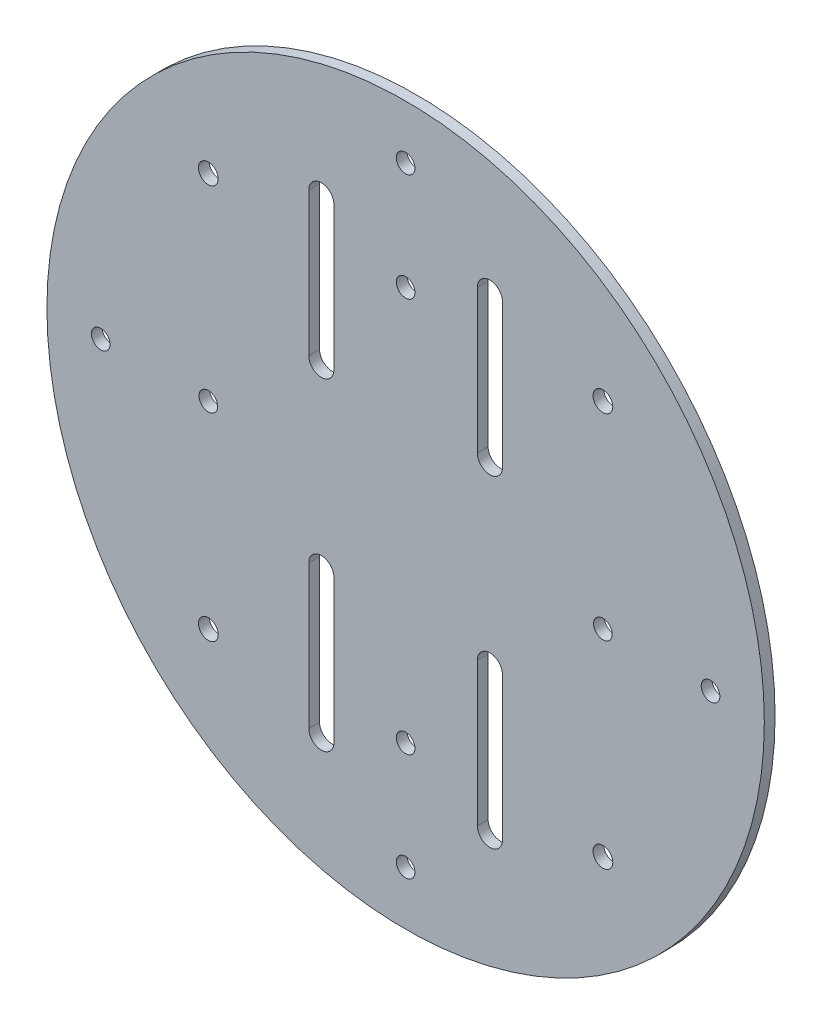
SolidWorks part; units mm, degrees
ref_plane "Ön Düzlem" through (0, 0, 0) normal (0, 0, 1) x (1, 0, 0)
ref_plane "Üst Düzlem" through (0, 0, 0) normal (0, 1, 0) x (1, 0, 0)
ref_plane "Sağ Düzlem" through (0, 0, 0) normal (1, 0, 0) x (0, 0, -1)
sketch "Çizim1" plane through (0, 0, 0) normal (0, 0, 1) x (1, 0, 0)
  circle A0 centre (0, 0) radius 100
  dimension "D1" = 200
extrude "Yükseklik-Ekstrüzyon1" add sketch "Çizim1" along normal blind 30
hole_wizard "M5 Helisarmal için Zıvana matkabı1" positions "Çizim7" profile "Çizim8" hole size "M5x0.8" standard "ANSI Metrik" end condition through all
sketch "Çizim7" plane through (0, 0, 30) normal (0, 0, 1) x (1, 0, 0)
  point P0 (-85, 0)
  point P2 (-55, 0)
  point P4 (0, 55)
  point P6 (0, 85)
  point P8 (55, 0)
  point P10 (85, 0)
  point P12 (0, -55)
  point P14 (0, -85)
  dimension "D1" = 85
  dimension "D2" = 55
  dimension "D3" = 55
  dimension "D4" = 85
  dimension "D5" = 85
  dimension "D6" = 55
  dimension "D7" = 85
  dimension "D8" = 55
sketch "Çizim8" plane through (-85, 0, 30) normal (1, 0, 0) x (0, -1, 0)
  line L0 (0, 0) -> (0, 30)
  line L1 (0, 30) -> (2.6, 30)
  line L2 (2.6, 30) -> (2.6, 0)
  line L5 (2.6, 0) -> (0, 0)
  line L11 (0, -6.35) -> (0, 107.95) construction
  dimension "Thru Hole Dia." = 5.2
  dimension "Thru Hole Depth" = 30
sketch "Çizim9" plane through (0, 0, 30) normal (0, 0, 1) x (1, 0, 0)
  line L0 (23.5, 65) -> (23.5, 25) construction
  line L1 (27, 65) -> (27, 25)
  line L2 (20, 65) -> (20, 25)
  line L3 (-23.5, 65) -> (-23.5, 25) construction
  line L4 (-20, 65) -> (-20, 25)
  line L5 (-27, 65) -> (-27, 25)
  line L6 (-23.5, -25) -> (-23.5, -65) construction
  line L7 (-20, -25) -> (-20, -65)
  line L8 (-27, -25) -> (-27, -65)
  line L9 (23.5, -65) -> (23.5, -25) construction
  line L10 (20, -65) -> (20, -25)
  line L11 (27, -65) -> (27, -25)
  arc A0 (27, 65) -> (20, 65) centre (23.5, 65) ccw
  arc A1 (20, 25) -> (27, 25) centre (23.5, 25) ccw
  arc A2 (-20, 65) -> (-27, 65) centre (-23.5, 65) ccw
  arc A3 (-27, 25) -> (-20, 25) centre (-23.5, 25) ccw
  arc A4 (-20, -25) -> (-27, -25) centre (-23.5, -25) ccw
  arc A5 (-27, -65) -> (-20, -65) centre (-23.5, -65) ccw
  arc A6 (20, -65) -> (27, -65) centre (23.5, -65) ccw
  arc A7 (27, -25) -> (20, -25) centre (23.5, -25) ccw
  circle A8 centre (0, -55) radius 2.6 construction
  circle A9 centre (0, 0) radius 100 construction
  point P2 (23.5, 45)
  point P8 (-23.5, 45)
  point P15 (-23.5, -45)
  point P22 (23.5, -45)
  dimension "D2" = 40
  dimension "D11" = 50
  dimension "D13" = 65
  dimension "D1" = 7
  dimension "D3" = 40
  dimension "D4" = 7
  dimension "D5" = 7
  dimension "D6" = 40
  dimension "D7" = 40
  dimension "D8" = 7
  dimension "D9" = 40
  dimension "D10" = 50
  dimension "D12" = 20
  dimension "D14" = 65
extrude "Kes-Ekstrüzyon1" cut sketch "Çizim9" against normal through all
hole_wizard "M5 Boşluklu Delik2" positions "Çizim19" profile "Çizim18" hole size "M5" standard "ANSI Metrik" end condition through all
sketch "Çizim19" plane through (0, 0, 30) normal (0, 0, 1) x (1, 0, 0)
  point P0 (-55, 55)
  point P2 (55, 55)
  point P4 (55, -55)
  point P6 (-55, -55)
sketch "Çizim18" plane through (-55, 55, 30) normal (1, 0, 0) x (0, -1, 0)
  line L0 (0, 0) -> (0, 30)
  line L1 (0, 30) -> (2.75, 30)
  line L2 (2.75, 30) -> (2.75, 0)
  line L5 (2.75, 0) -> (0, 0)
  line L11 (0, -6.35) -> (0, 107.95) construction
  dimension "Thru Hole Dia." = 5.5
  dimension "Thru Hole Depth" = 30
sketch "Çizim20" plane through (0, 0, 30) normal (0, 0, 1) x (1, 0, 0)
  circle A0 centre (0, 8.4795) radius 183.5376
extrude "Kes-Ekstrüzyon2" cut sketch "Çizim20" against normal blind 27
